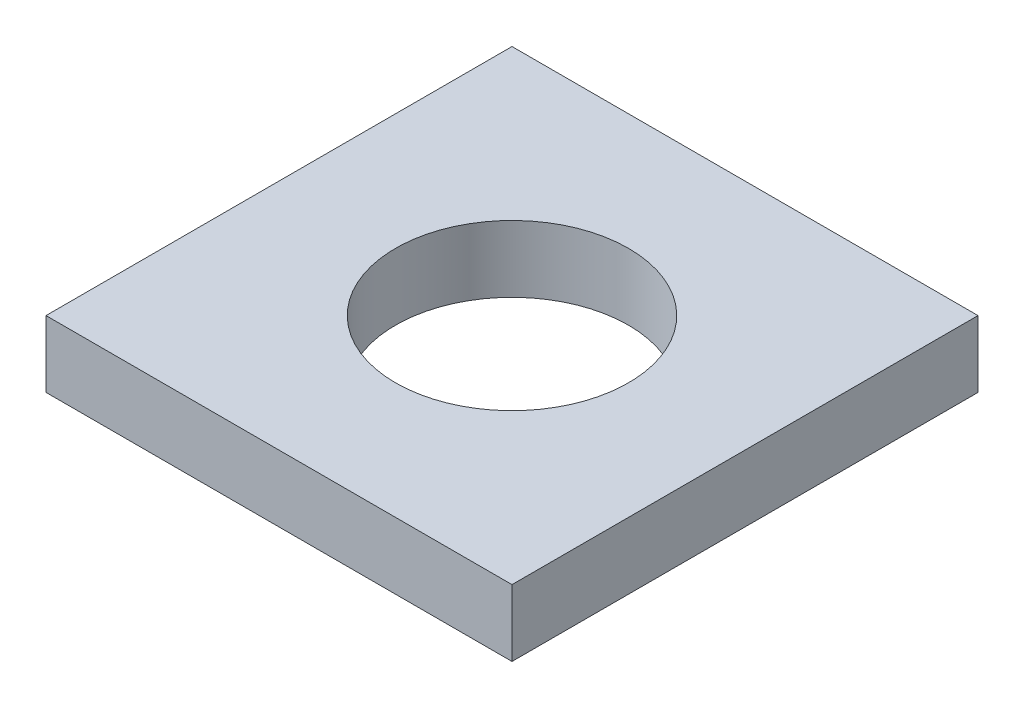
SolidWorks part; units mm, degrees
ref_plane "前视基准面" through (0, 0, 0) normal (0, 0, 1) x (1, 0, 0)
ref_plane "上视基准面" through (0, 0, 0) normal (0, 1, 0) x (1, 0, 0)
ref_plane "右视基准面" through (0, 0, 0) normal (1, 0, 0) x (0, 0, -1)
other "Configuration Table"
sketch "草图1" plane through (0, 0, 0) normal (0, 1, 0) x (1, 0, 0)
  line L7 (-3.5, 3.5) -> (3.5, 3.5)
  line L8 (-3.5, 3.5) -> (-3.5, -3.5)
  line L9 (-3.5, -3.5) -> (3.5, -3.5)
  line L10 (3.5, 3.5) -> (3.5, -3.5)
  line L11 (-3.5, 3.5) -> (3.5, -3.5) construction
  line L12 (-3.5, -3.5) -> (3.5, 3.5) construction
  circle A0 centre (0, 0) radius 1.75
  point P0 (0, 0)
  point P5 (0, 0)
  dimension "D1" = 3.5
  dimension "D4" = 7
extrude "凸台-拉伸1" add sketch "草图1" along normal blind 1
